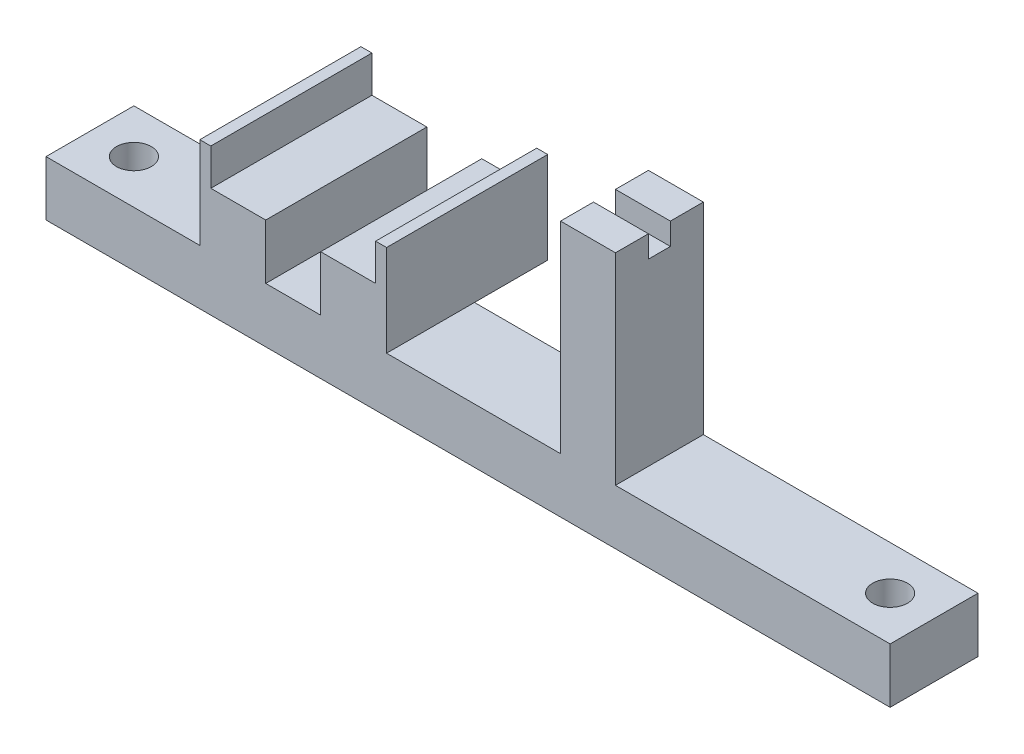
SolidWorks part; units mm, degrees
ref_plane "Front Plane" through (0, 0, 0) normal (0, 0, 1) x (1, 0, 0)
ref_plane "Top Plane" through (0, 0, 0) normal (0, 1, 0) x (1, 0, 0)
ref_plane "Right Plane" through (0, 0, 0) normal (1, 0, 0) x (0, 0, -1)
sketch "Sketch1" plane through (0, 0, 0) normal (0, 1, 0) x (1, 0, 0)
  line L1 (-93.7314, 47.1962) -> (136.7686, 47.1962)
  line L2 (-93.7314, 47.1962) -> (-93.7314, 23.1962)
  line L3 (-93.7314, 23.1962) -> (136.7686, 23.1962)
  line L4 (136.7686, 47.1962) -> (136.7686, 23.1962)
  dimension "D1" = 230.5
  dimension "D2" = 24
extrude "Boss-Extrude1" add sketch "Sketch1" along normal blind 15
sketch "Sketch2" plane through (0, 15, 0) normal (0, 1, 0) x (1, 0, 0)
  line L4 (-93.7314, 23.1962) -> (136.7686, 23.1962) construction
  circle A0 centre (-81.7314, 35.1962) radius 4.75
  circle A1 centre (124.7686, 35.1962) radius 4.75
  dimension "D1" = 206.5
  dimension "D3" = 9.5
  dimension "D2" = 9.5
  dimension "D5" = 12
  dimension "D6" = 12
extrude "Cut-Extrude1" cut sketch "Sketch2" against normal blind 15
sketch "Sketch4" plane through (0, 15, 0) normal (0, 1, 0) x (1, 0, 0)
  line L7 (-93.7314, 23.1962) -> (136.7686, 23.1962) construction
  line L8 (-51.7314, 23.1962) -> (-33.7314, 23.1962)
  line L9 (-51.7314, 23.1962) -> (-51.7314, 67.1962)
  line L10 (-51.7314, 67.1962) -> (-33.7314, 67.1962)
  line L11 (-33.7314, 23.1962) -> (-33.7314, 67.1962)
  line L12 (-93.7314, 47.1962) -> (-93.7314, 23.1962) construction
  line L14 (-18.7314, 67.1962) -> (-0.7314, 67.1962)
  line L15 (-18.7314, 67.1962) -> (-18.7314, 23.1962)
  line L16 (-18.7314, 23.1962) -> (-0.7314, 23.1962)
  line L17 (-0.7314, 67.1962) -> (-0.7314, 23.1962)
  dimension "D1" = 42
  dimension "D2" = 18
  dimension "D3" = 44
  dimension "D4" = 15
  dimension "D5" = 18
  dimension "D6" = 44
extrude "Boss-Extrude2" add sketch "Sketch4" along normal blind 15
sketch "Sketch5" plane through (0, 15, 0) normal (0, 1, 0) x (1, 0, 0)
  line L0 (136.7686, 47.1962) -> (-0.7314, 47.1962) construction
  line L1 (46.7686, 47.1962) -> (61.7686, 47.1962)
  line L2 (46.7686, 47.1962) -> (46.7686, 23.1962)
  line L3 (46.7686, 23.1962) -> (61.7686, 23.1962)
  line L4 (61.7686, 47.1962) -> (61.7686, 23.1962)
  line L5 (-33.7314, 23.1962) -> (-18.7314, 23.1962) construction
  line L7 (136.7686, 23.1962) -> (136.7686, 47.1962) construction
  dimension "D1" = 15
  dimension "D2" = 75
extrude "Boss-Extrude3" add sketch "Sketch5" along normal blind 49
sketch "Sketch6" plane through (0, 64, 0) normal (0, 1, 0) x (1, 0, 0)
  line L0 (61.7686, 23.1962) -> (61.7686, 47.1962) construction
  line L1 (46.7686, 47.1962) -> (61.7686, 47.1962)
  line L2 (46.7686, 47.1962) -> (46.7686, 38.1962)
  line L3 (46.7686, 38.1962) -> (61.7686, 38.1962)
  line L4 (61.7686, 47.1962) -> (61.7686, 38.1962)
  line L5 (61.7686, 23.1962) -> (61.7686, 47.1962) construction
  line L6 (46.7686, 23.1962) -> (61.7686, 23.1962)
  line L7 (46.7686, 23.1962) -> (46.7686, 32.1962)
  line L8 (46.7686, 32.1962) -> (61.7686, 32.1962)
  line L9 (61.7686, 23.1962) -> (61.7686, 32.1962)
  dimension "D1" = 9
  dimension "D2" = 9
extrude "Boss-Extrude4" add sketch "Sketch6" along normal blind 6
sketch "Sketch7" plane through (0, 30, 0) normal (0, 1, 0) x (1, 0, 0)
  line L0 (-51.7314, 23.1962) -> (-33.7314, 23.1962) construction
  line L1 (-51.7314, 67.1962) -> (-48.7314, 67.1962)
  line L2 (-51.7314, 67.1962) -> (-51.7314, 23.1962)
  line L3 (-51.7314, 23.1962) -> (-48.7314, 23.1962)
  line L4 (-48.7314, 67.1962) -> (-48.7314, 23.1962)
  line L5 (-18.7314, 23.1962) -> (-0.7314, 23.1962) construction
  line L6 (-0.7314, 67.1962) -> (-3.7314, 67.1962)
  line L7 (-0.7314, 67.1962) -> (-0.7314, 23.1962)
  line L8 (-0.7314, 23.1962) -> (-3.7314, 23.1962)
  line L9 (-3.7314, 67.1962) -> (-3.7314, 23.1962)
  dimension "D1" = 3
  dimension "D2" = 3
extrude "Boss-Extrude5" add sketch "Sketch7" along normal blind 10
